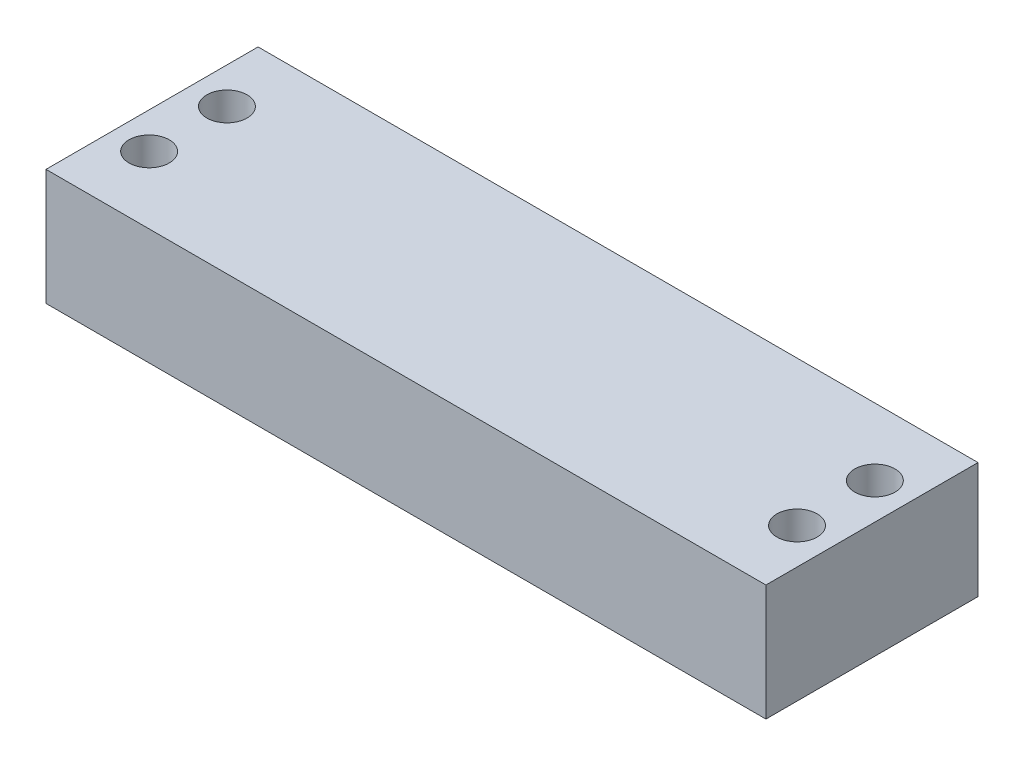
SolidWorks part; units mm, degrees
ref_plane "Front Plane" through (0, 0, 0) normal (0, 0, 1) x (1, 0, 0)
ref_plane "Top Plane" through (0, 0, 0) normal (0, 1, 0) x (1, 0, 0)
ref_plane "Right Plane" through (0, 0, 0) normal (1, 0, 0) x (0, 0, -1)
sketch "Sketch1" plane through (0, 0, 0) normal (0, 1, 0) x (1, 0, 0)
  line L0 (0, 10.9) -> (74, 10.9) construction
  line L1 (0, 0) -> (74, 0)
  line L2 (0, 0) -> (0, 21.8)
  line L3 (0, 21.8) -> (74, 21.8)
  line L4 (74, 0) -> (74, 21.8)
  line L5 (37, 21.8) -> (37, 0) construction
  line L6 (0, 6.9) -> (74, 6.9) construction
  line L7 (3.7, 21.8) -> (3.7, 0) construction
  circle A0 centre (3.7, 6.9) radius 2.0701
  circle A1 centre (3.7, 14.9) radius 2.0701
  circle A2 centre (70.3, 6.9) radius 2.0701
  circle A3 centre (70.3, 14.9) radius 2.0701
  point P13 (3.7, 6.9)
  point P19 (0, 0)
  dimension "D3" = 4.1402
  dimension "D1" = 74
  dimension "D2" = 21.8
  dimension "D4" = 33.3
  dimension "D5" = 4
extrude "Boss-Extrude1" add sketch "Sketch1" along normal blind 11.938
ref_plane "Plane1" through (0, 0, -10.9) normal (0, 0, 1) x (1, 0, 0)
ref_plane "Plane2" through (37, 0, 0) normal (1, 0, 0) x (0, 0, -1)
